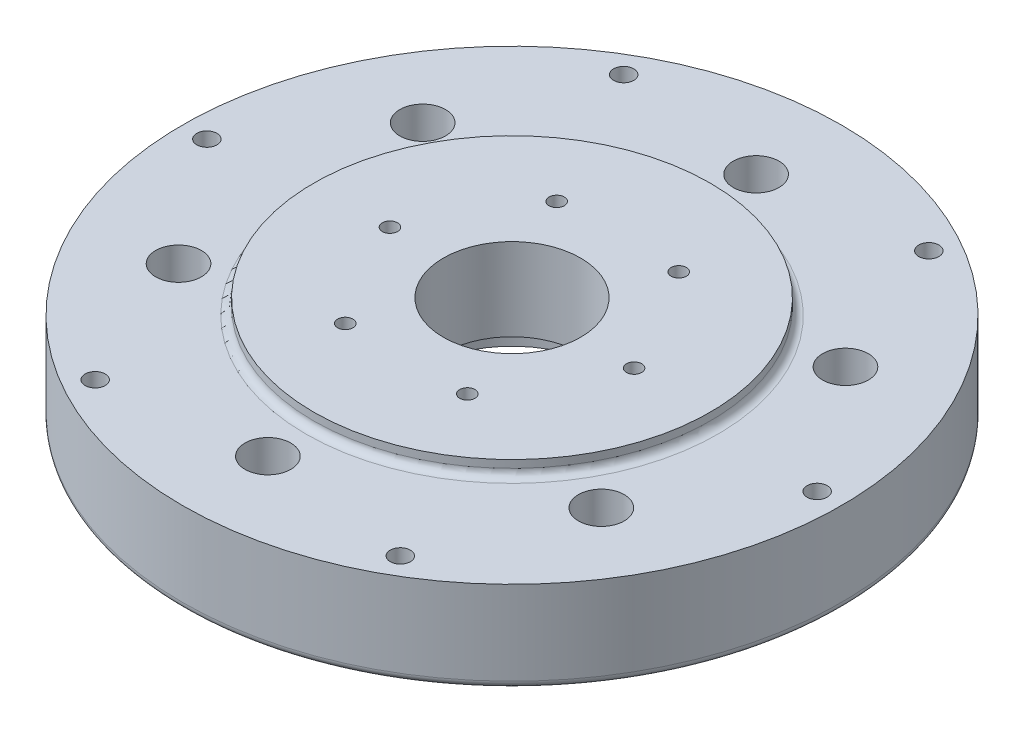
SolidWorks part; units mm, degrees
material "延性铁"
ref_plane "前视基准面" through (0, 0, 0) normal (0, 0, 1) x (1, 0, 0)
ref_plane "上视基准面" through (0, 0, 0) normal (0, 1, 0) x (1, 0, 0)
ref_plane "右视基准面" through (0, 0, 0) normal (1, 0, 0) x (0, 0, -1)
sketch "草图1" plane through (0, 0, 0) normal (0, 1, 0) x (1, 0, 0)
  circle A0 centre (0, 0) radius 108
  circle A1 centre (0, 0) radius 22.5
  dimension "D1" = 216
  dimension "D2" = 45
extrude "凸台-拉伸1" add sketch "草图1" along normal blind 30
sketch "草图2" plane through (0, 30, 0) normal (0, 1, 0) x (1, 0, 0)
  circle A0 centre (0, 0) radius 22.5 construction
  circle A1 centre (0, 0) radius 22.5
  circle A2 centre (0, 0) radius 65
  dimension "D1" = 130
extrude "凸台-拉伸2" add sketch "草图2" along normal blind 5
sketch "草图6" plane through (0, 0, 0) normal (0, -1, 0) x (1, 0, 0)
  circle A0 centre (0, 0) radius 30
  dimension "D1" = 60
extrude "切除-拉伸2" cut sketch "草图6" against normal blind 8
fillet "圆角1" radius 2.5 2 edges at (0, 30, 65) (0, 0, 108)
sketch "草图3" plane through (0, 30, 0) normal (0, 1, 0) x (1, 0, 0)
  circle A0 centre (0, 80) radius 7.5
  dimension "D1" = 80
  dimension "D2" = 15
extrude "切除-拉伸1" cut sketch "草图3" against normal through all
hole_wizard "M6 螺纹孔1" positions "草图4" profile "草图5" tap size "M6" standard "GB" end condition through all
sketch "草图4" plane through (0, 0, 0) normal (0, -1, 0) x (-1, 0, 0)
  point P0 (40, 0)
  dimension "D1" = 40
sketch "草图5" plane through (-40, 0, 0) normal (1, 0, 0) x (0, 0, -1)
  line L0 (0, 0) -> (0, 35)
  line L1 (0, 35) -> (2.5, 35)
  line L2 (2.5, 35) -> (2.5, 0)
  line L5 (2.5, 0) -> (0, 0)
  line L11 (0, -6.35) -> (0, 107.95) construction
  dimension "通孔螺纹孔钻头直径" = 5
  dimension "通孔螺纹孔钻头深度" = 35
cosmetic thread "孔螺蚊线2" parameters "D2"=6
hole_wizard "打孔尺寸(%根据)内六角圆柱头螺钉的类型2" positions "草图8" profile "草图9" counterbore size "M6" standard "GB" end condition through all
sketch "草图8" plane through (0, 0, 0) normal (0, -1, 0) x (-1, 0, 0)
  point P0 (100, 0)
  dimension "D1" = 100
sketch "草图9" plane through (-100, 0, 0) normal (1, 0, 0) x (0, 0, -1)
  line L0 (0, 0) -> (0, 35)
  line L1 (0, 35) -> (3.3, 35)
  line L3 (3.3, 35) -> (3.3, 7)
  line L4 (3.3, 7) -> (5.5, 7)
  line L5 (5.5, 7) -> (5.5, 0)
  line L7 (5.5, 0) -> (0, 0)
  line L11 (0, -6.35) -> (0, 107.95) construction
  dimension "通孔孔直径" = 6.6
  dimension "通孔孔深度" = 35
  dimension "柱形沉头孔直径" = 11
  dimension "柱形沉头孔深度" = 7
hole_wizard "M3 螺纹孔1" positions "草图10" profile "草图11" tap size "M3" standard "GB"
sketch "草图10" plane through (0, 8, 0) normal (0, -1, 0) x (-1, 0, 0)
  point P0 (0, 25)
  dimension "D1" = 25
cosmetic thread "孔螺蚊线1" parameters "D1"=6, "D2"=3
sketch "草图11" plane through (0, 8, -25) normal (1, 0, 0) x (0, 0, -1)
  line L0 (0, 0) -> (0, 8.2511)
  line L1 (0, 8.2511) -> (1.25, 7.5)
  line L2 (1.25, 7.5) -> (1.25, 0)
  line L5 (1.25, 0) -> (0, 0)
  line L10 (0, 8.2511) -> (-1.25, 7.5) construction
  line L11 (0, -6.35) -> (0, 107.95) construction
  dimension "螺纹孔钻头直径" = 2.5
  dimension "螺纹孔钻头深度" = 7.5
  dimension "导头角度" = 118
pattern_circular "阵列(圆周)1" count 6 over 360 about axis through (0, 0, 0) along (0, 1, 0) of "切除-拉伸1", "打孔尺寸(%根据)内六角圆柱头螺钉的类型2", "M6 螺纹孔1", "M3 螺纹孔1"
